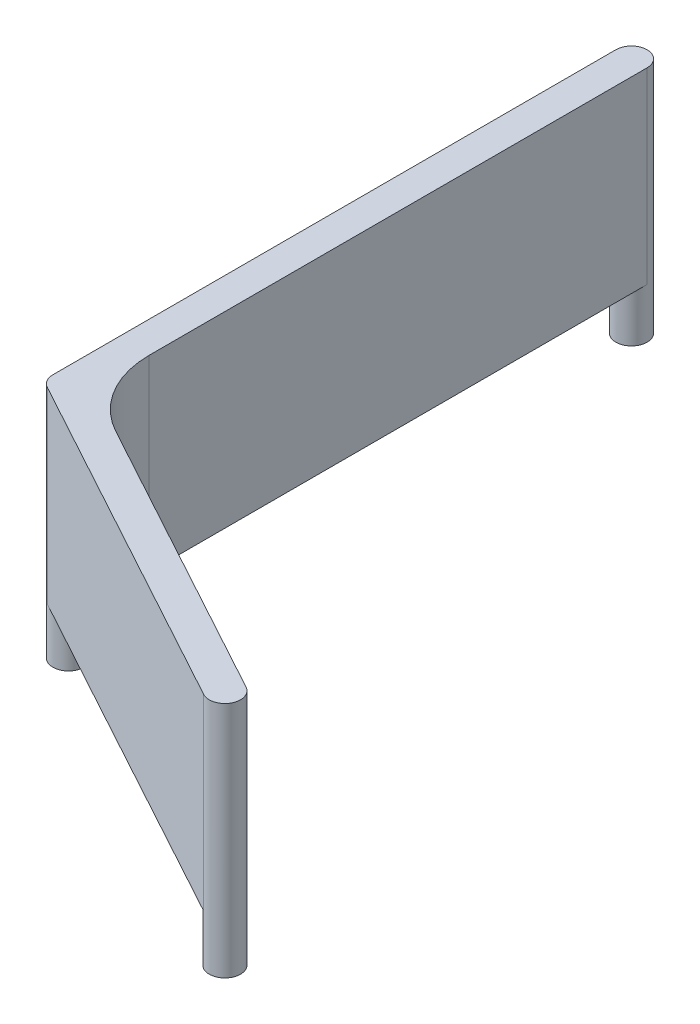
SolidWorks part; units mm, degrees
material "ABS"
ref_plane "Front Plane" through (0, 0, 0) normal (0, 0, 1) x (1, 0, 0)
ref_plane "Top Plane" through (0, 0, 0) normal (0, 1, 0) x (1, 0, 0)
ref_plane "Right Plane" through (0, 0, 0) normal (1, 0, 0) x (0, 0, -1)
sketch "Sketch1" plane through (0, 0, 0) normal (0, 1, 0) x (1, 0, 0)
  line L0 (0, 0) -> (0, 114.3) construction
  line L1 (-3.175, 0) -> (-3.175, 114.3)
  line L2 (3.175, 1.8848) -> (3.175, 114.3)
  line L3 (0, 0) -> (69.85, -38.1) construction
  line L4 (3.175, 1.8848) -> (71.3704, -35.3127)
  line L5 (-1.5204, -2.7873) -> (68.3296, -40.8873)
  arc A0 (-3.175, 0) -> (-1.5204, -2.7873) centre (0, 0) ccw
  arc A1 (3.175, 114.3) -> (-3.175, 114.3) centre (0, 114.3) ccw
  arc A3 (68.3296, -40.8873) -> (71.3704, -35.3127) centre (69.85, -38.1) ccw
  point P3 (0, 57.15)
  point P8 (34.925, -19.05)
  point P15 (0, 0)
  point P16 (0, 0)
  dimension "D1" = 6.35
  dimension "D2" = 6.35
  dimension "D3" = 152.4
  dimension "D4" = 114.3
  dimension "D5" = 69.85
extrude "Boss-Extrude1" add sketch "Sketch1" along normal blind 38.1
sketch "Sketch2" plane through (0, 0, 0) normal (0, -1, 0) x (-1, 0, 0)
  circle A0 centre (0, 114.3) radius 3.175
  circle A1 centre (0, 0) radius 3.175
  circle A2 centre (-69.85, -38.1) radius 3.175
extrude "Boss-Extrude2" add sketch "Sketch2" along normal blind 10.16
fillet "Fillet1" radius 19.05 1 edges at (3.175, 19.05, -1.8848)
